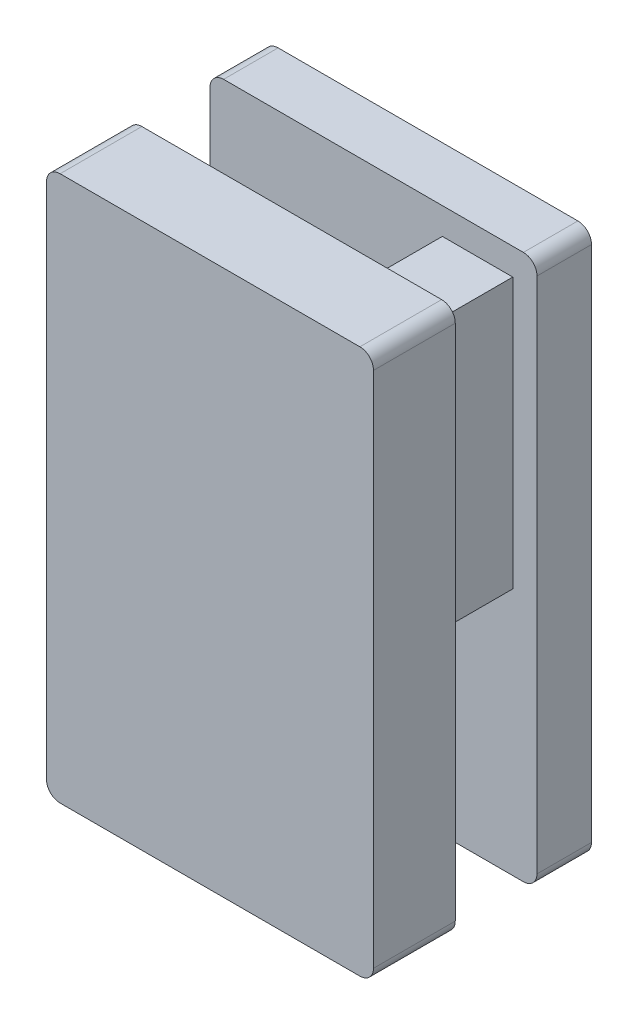
SolidWorks part; units mm, degrees
ref_plane "Front Plane" through (0, 0, 0) normal (0, 0, 1) x (1, 0, 0)
ref_plane "Top Plane" through (0, 0, 0) normal (0, 1, 0) x (1, 0, 0)
ref_plane "Right Plane" through (0, 0, 0) normal (1, 0, 0) x (0, 0, -1)
sketch "Sketch1" plane through (0, 0, 0) normal (0, 0, 1) x (1, 0, 0)
  line L1 (62.5859, -153) -> (74.5859, -153)
  line L2 (62.5859, -153) -> (62.5859, -173)
  line L3 (62.5859, -173) -> (74.5859, -173)
  line L4 (74.5859, -153) -> (74.5859, -173)
  line L5 (68.5859, -263) -> (68.5859, 0) construction
  dimension "D1" = 12
  dimension "D2" = 20
  dimension "D3" = 6
extrude "Boss-Extrude1" add sketch "Sketch1" along normal blind 2
sketch "Sketch2" plane through (0, 0, 2) normal (0, 0, 1) x (1, 0, 0)
  line L1 (73.6964, -153.9784) -> (71.1128, -153.9784)
  line L2 (73.6964, -153.9784) -> (73.6964, -163.8882)
  line L3 (73.6964, -163.8882) -> (71.1128, -163.8882)
  line L4 (71.1128, -153.9784) -> (71.1128, -163.8882)
extrude "Boss-Extrude2" add sketch "Sketch2" along normal blind 3
sketch "Sketch3" plane through (0, 0, 5) normal (0, 0, 1) x (1, 0, 0)
  line L4 (62.5859, -153) -> (62.5859, -173)
  line L5 (74.5859, -153) -> (62.5859, -153)
  line L6 (74.5859, -173) -> (74.5859, -153)
  line L7 (62.5859, -173) -> (74.5859, -173)
  line L8 (62.5859, -153) -> (62.5859, -173)
  line L9 (74.5859, -153) -> (62.5859, -153)
  line L10 (74.5859, -173) -> (74.5859, -153)
  line L11 (62.5859, -173) -> (74.5859, -173)
  dimension "D1" = 0
extrude "Boss-Extrude3" add sketch "Sketch3" along normal blind 3
fillet "Fillet1" radius 0.5 8 edges at (74.5859, -153, 6.5) (74.5859, -153, 1) (62.5859, -153, 6.5) (62.5859, -153, 1) (62.5859, -173, 6.5) (74.5859, -173, 6.5) (74.5859, -173, 1) (62.5859, -173, 1)
